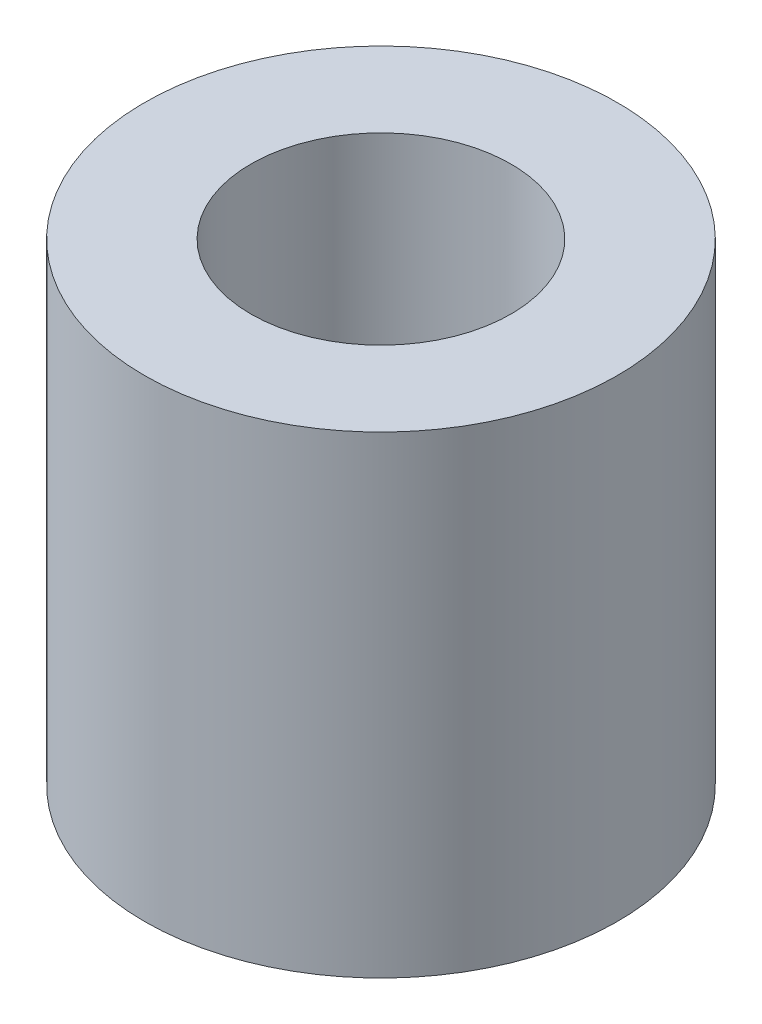
SolidWorks part; units mm, degrees
material "Brass"
ref_plane "Front Plane" through (0, 0, 0) normal (0, 0, 1) x (1, 0, 0)
ref_plane "Top Plane" through (0, 0, 0) normal (0, 1, 0) x (1, 0, 0)
ref_plane "Right Plane" through (0, 0, 0) normal (1, 0, 0) x (0, 0, -1)
sketch "Sketch1" plane through (0, 0, 0) normal (0, 1, 0) x (1, 0, 0)
  circle A0 centre (0, 0) radius 3
  dimension "D1" = 6
extrude "Boss-Extrude1" add sketch "Sketch1" along normal blind 6
hole_wizard "M4x0.7 Tapped Hole1" positions "Sketch2" profile "Sketch3" tap size "M4x0.7" standard "ANSI Metric" end condition through all
sketch "Sketch2" plane through (0, 6, 0) normal (0, 1, 0) x (1, 0, 0)
  point P0 (0, 0)
sketch "Sketch3" plane through (0, 6, 0) normal (1, 0, 0) x (0, 0, 1)
  line L0 (0, 0) -> (0, 6)
  line L1 (0, 6) -> (1.65, 6)
  line L2 (1.65, 6) -> (1.65, 0)
  line L5 (1.65, 0) -> (0, 0)
  line L11 (0, -6.35) -> (0, 107.95) construction
  dimension "Thru Tap Drill Dia." = 3.3
  dimension "Thru Tap Drill Depth" = 6
cosmetic thread "Hole Thread1"
